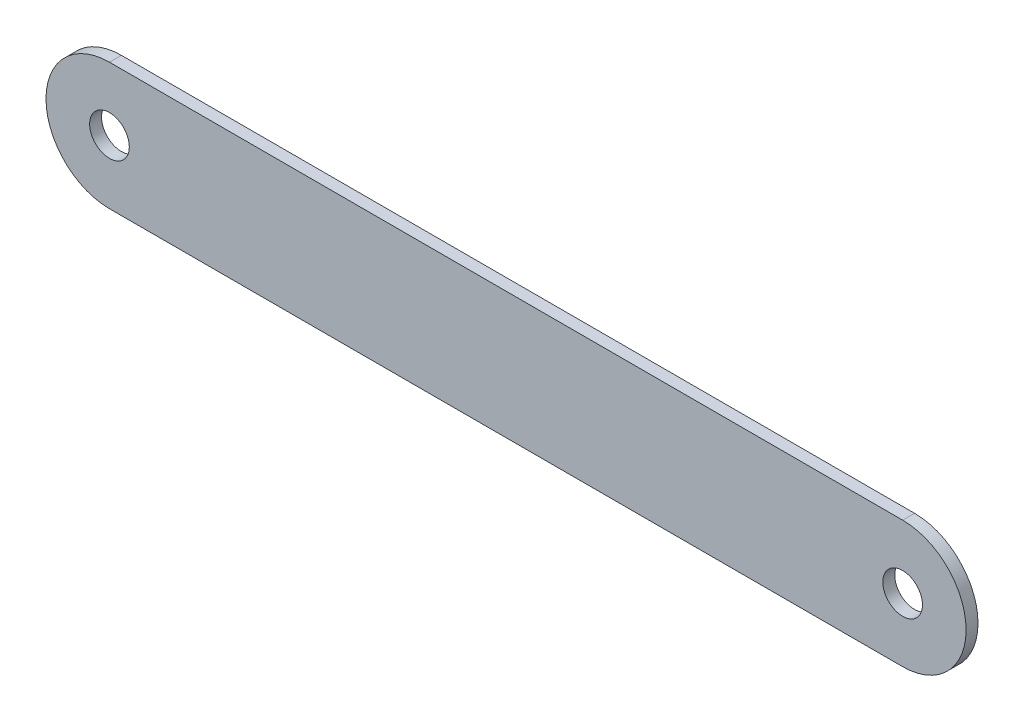
SolidWorks part; units mm, degrees
ref_plane "Front" through (0, 0, 0) normal (0, 0, 1) x (1, 0, 0)
ref_plane "Top" through (0, 0, 0) normal (0, 1, 0) x (1, 0, 0)
ref_plane "Right" through (0, 0, 0) normal (1, 0, 0) x (0, 0, -1)
sketch "草图1" plane through (0, 0, 0) normal (0, 0, 1) x (1, 0, 0)
  line L0 (0, 0) -> (-200, 0) construction
  line L1 (0, -16) -> (-200, -16)
  line L2 (0, 16) -> (-200, 16)
  arc A0 (0, -16) -> (0, 16) centre (0, 0) ccw
  arc A1 (-200, 16) -> (-200, -16) centre (-200, 0) ccw
  point P3 (-100, 0)
  dimension "D1" = 200
  dimension "D2" = 16
extrude "凸台-拉伸1" add sketch "草图1" along normal blind 3
sketch "草图2" plane through (0, 0, 3) normal (0, 0, 1) x (1, 0, 0)
  circle A0 centre (-200, 0) radius 5
  circle A1 centre (0, 0) radius 5
  dimension "D1" = 10
  dimension "D2" = 10
extrude "切除-拉伸1" cut sketch "草图2" against normal blind 3
